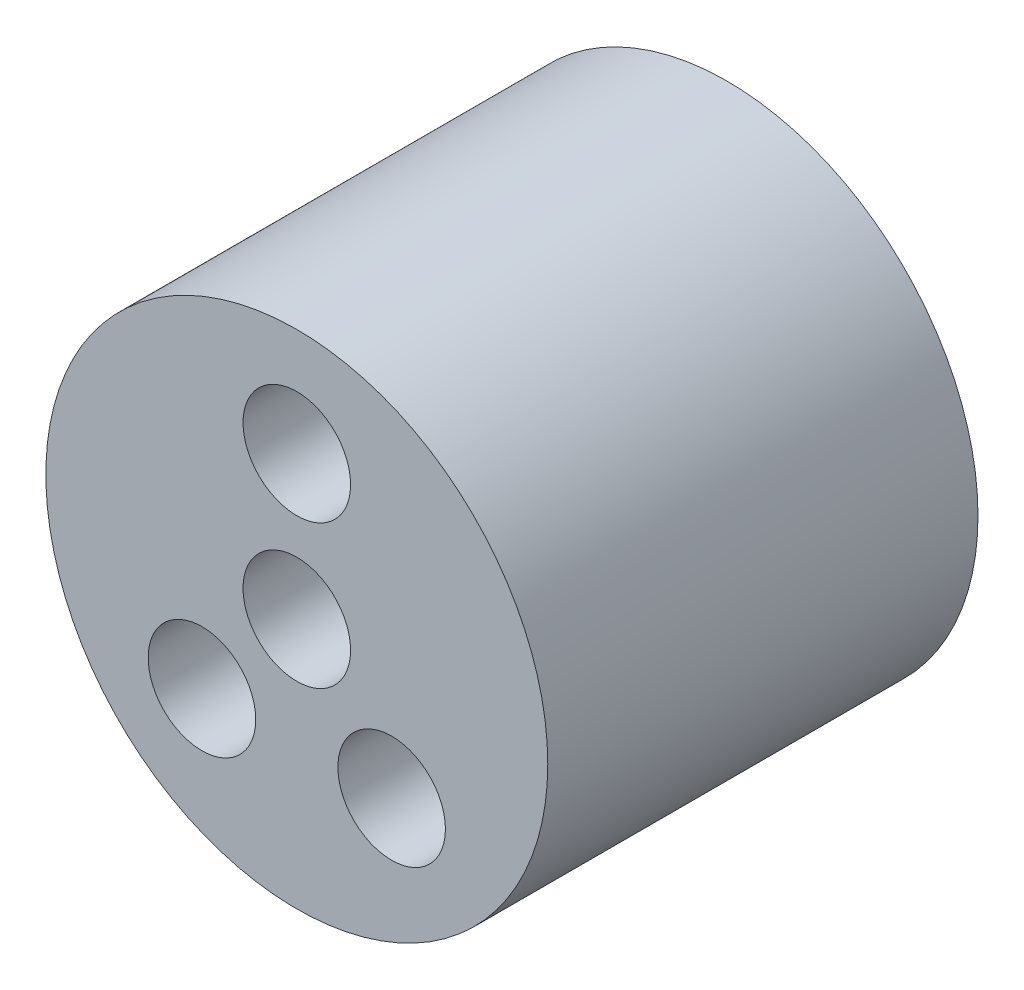
SolidWorks part; units mm, degrees
ref_plane "Front Plane" through (0, 0, 0) normal (0, 0, 1) x (1, 0, 0)
ref_plane "Top Plane" through (0, 0, 0) normal (0, 1, 0) x (1, 0, 0)
ref_plane "Right Plane" through (0, 0, 0) normal (1, 0, 0) x (0, 0, -1)
sketch "Sketch1" plane through (0, 0, 0) normal (0, 0, 1) x (1, 0, 0)
  line L0 (0, 196.5424) -> (0, -197.3512) construction
  line L1 (-181.9837, 0) -> (169.0426, 0) construction
  circle A0 centre (0, 0) radius 140
  circle A1 centre (0, 0) radius 80 construction
  circle A2 centre (0, 0) radius 30
  circle A3 centre (0, 80) radius 30
  circle A4 centre (52.915, -60) radius 30
  circle A5 centre (-52.915, -60) radius 30
  point P15 (0, 0)
  point P16 (0, 0)
  dimension "D1" = 280
  dimension "D2" = 60
  dimension "D3" = 80
  dimension "D4" = 60
extrude "Boss-Extrude1" add sketch "Sketch1" along normal blind 240
